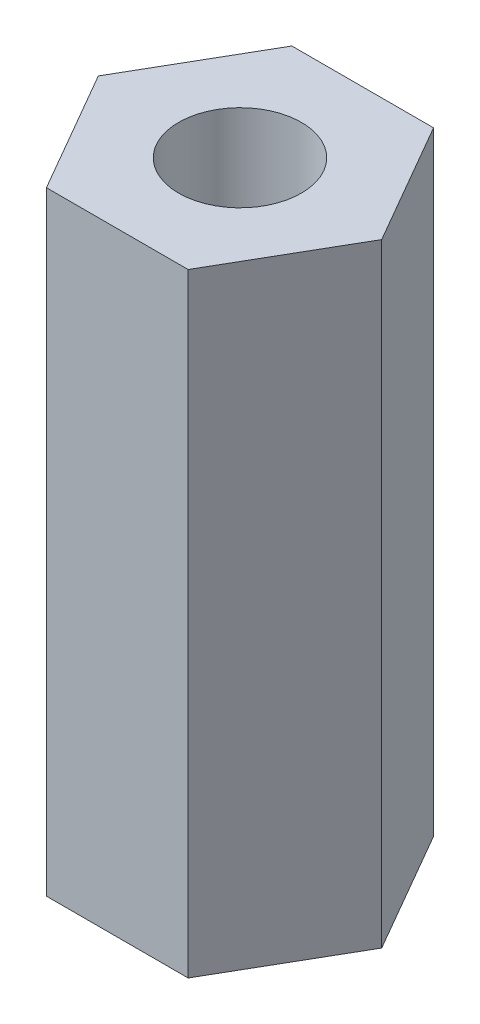
SolidWorks part; units mm, degrees
ref_plane "Front Plane" through (0, 0, 0) normal (0, 0, 1) x (1, 0, 0)
ref_plane "Top Plane" through (0, 0, 0) normal (0, 1, 0) x (1, 0, 0)
ref_plane "Right Plane" through (0, 0, 0) normal (1, 0, 0) x (0, 0, -1)
sketch "Sketch1" plane through (0, 0, 0) normal (0, 1, 0) x (1, 0, 0)
  line L1 (7.3323, 0) -> (3.6662, 6.35)
  line L2 (3.6662, 6.35) -> (-3.6662, 6.35)
  line L3 (-3.6662, 6.35) -> (-7.3323, 0)
  line L4 (-7.3323, 0) -> (-3.6662, -6.35)
  line L5 (-3.6662, -6.35) -> (3.6662, -6.35)
  line L6 (3.6662, -6.35) -> (7.3323, 0)
  circle A1 centre (0, 0) radius 3.175
  circle A2 centre (0, 0) radius 6.35 construction
extrude "Boss-Extrude1" add sketch "Sketch1" along normal blind 31.75
